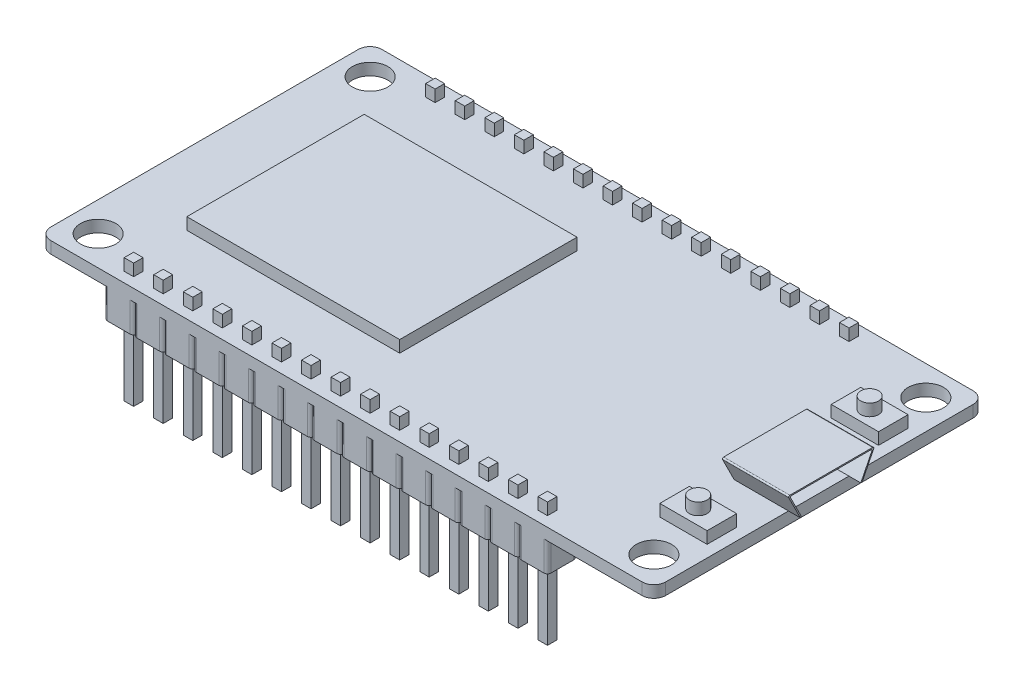
SolidWorks part; units mm, degrees
ref_plane "前视基准面" through (0, 0, 0) normal (0, 0, 1) x (1, 0, 0)
ref_plane "上视基准面" through (0, 0, 0) normal (0, 1, 0) x (1, 0, 0)
ref_plane "右视基准面" through (0, 0, 0) normal (1, 0, 0) x (0, 0, -1)
other "Configuration Table"
sketch "草图1" plane through (0, 0, 0) normal (0, 1, 0) x (1, 0, 0)
  line L0 (0, 0) -> (-18936.8297, 0) construction
  line L1 (0, 0) -> (0, -18936.8297) construction
  line L2 (-26, -14) -> (-26, 14)
  line L3 (-26, 14) -> (26, 14)
  line L4 (26, 14) -> (26, -14)
  line L5 (-26, -14) -> (26, -14)
  circle A0 centre (-23.5, -11.5) radius 1.5
  circle A1 centre (23.5, -11.5) radius 1.5
  circle A2 centre (23.5, 11.5) radius 1.5
  circle A3 centre (-23.5, 11.5) radius 1.5
  point P10 (26, 0)
  point P11 (-26, 0)
  point P15 (-16.0179, -2.0506)
  dimension "D3" = 3
  dimension "D1" = 52
  dimension "D2" = 28
  dimension "D4" = 2.5
  dimension "D5" = 2.5
extrude "凸台-拉伸1" add sketch "草图1" along normal blind 1
fillet "圆角1" radius 1 4 edges at (-26, 0.5, -14) (26, 0.5, -14) (26, 0.5, 14) (-26, 0.5, 14)
sketch "草图2" plane through (0, 0, 0) normal (0, 1, 0) x (1, 0, 0)
  line L0 (0, 0) -> (-50000, 0) construction
  line L1 (0, 0) -> (0, -50000) construction
  line L2 (-20, 7.5) -> (-20, -7.5)
  line L3 (-20, -7.5) -> (-2, -7.5)
  line L4 (-2, -7.5) -> (-2, 7.5)
  line L5 (-2, 7.5) -> (-20, 7.5)
  line L6 (-26, 13) -> (-26, -13) construction
  dimension "D1" = 6
  dimension "D2" = 18
  dimension "D3" = 15
extrude "凸台-拉伸2" add sketch "草图2" along normal blind 2
ref_plane "基准面1" through (26, 0, 0) normal (1, 0, 0) x (0, 0, -1)
sketch "草图3" plane through (26, 0, 0) normal (1, 0, 0) x (0, 0, -1)
  line L0 (0, 0) -> (0, -50000) construction
  line L1 (0, 0) -> (-50000, 0) construction
  line L4 (-7.5, 1) -> (7.5, 1) construction
  line L5 (2.5, 1) -> (3.5, 3)
  line L6 (3.5, 3) -> (-3.5, 3)
  line L7 (-3.5, 3) -> (-2.5, 1)
  line L8 (-2.6118, 1) -> (-3.6618, 3.1)
  line L9 (-3.6618, 3.1) -> (3.6618, 3.1)
  line L10 (3.6618, 3.1) -> (2.6118, 1)
  line L11 (2.6118, 1) -> (2.5, 1)
  line L12 (-2.5, 1) -> (-2.6118, 1)
  dimension "D2" = 5
  dimension "D3" = 7
  dimension "D4" = 0.1
  dimension "D5" = 0.1
  dimension "D6" = 0.1
extrude "凸台-拉伸3" add sketch "草图3" along normal blind 1 and the other way blind 4.5
ref_plane "基准面2" through (21.5, 0, 0) normal (1, 0, 0) x (0, 0, -1)
sketch "草图4" plane through (21.5, 0, 0) normal (1, 0, 0) x (0, 0, -1)
  line L0 (-3.6618, 3.1) -> (-2.6118, 1)
  line L1 (-2.6118, 1) -> (2.6118, 1)
  line L2 (2.6118, 1) -> (3.6618, 3.1)
  line L3 (3.6618, 3.1) -> (-3.6618, 3.1)
extrude "凸台-拉伸4" add sketch "草图4" against normal blind 0.1
fillet "圆角2" radius 0.1 4 edges at (24.25, 3, -3.5) (24.2, 3.1, -3.6618) (24.25, 3, 3.5) (24.2, 3.1, 3.6618)
sketch "草图5" plane through (0, 0, 0) normal (0, 1, 0) x (1, 0, 0)
  line L0 (0, 0) -> (-50000, 0) construction
  line L1 (21, 8.5) -> (21, 6)
  line L2 (21, 6) -> (25, 6)
  line L3 (25, 6) -> (25, 8.5)
  line L4 (25, 8.5) -> (21, 8.5)
  line L5 (25, -6) -> (25, -8.5)
  line L6 (21, -6) -> (25, -6)
  line L7 (21, -8.5) -> (21, -6)
  line L8 (25, -8.5) -> (21, -8.5)
  line L10 (26, -13) -> (26, -2.6118) construction
  line L11 (-25, -14) -> (25, -14) construction
  dimension "D1" = 4
  dimension "D2" = 2.5
  dimension "D3" = 1
  dimension "D4" = 5.5
extrude "凸台-拉伸5" add sketch "草图5" along normal blind 2
sketch "草图6" plane through (0, 0, 0) normal (0, 1, 0) x (1, 0, 0)
  line L0 (0, 0) -> (-50000, 0) construction
  line L1 (23, 6) -> (23, -49994) construction
  line L2 (21, 6) -> (25, 6) construction
  line L3 (25, 7.25) -> (-49975, 7.25) construction
  line L4 (25, 6) -> (25, 8.5) construction
  circle A0 centre (23, 7.25) radius 0.75
  circle A1 centre (23, -7.25) radius 0.75
  point P7 (23, 6)
  point P12 (25, 7.25)
  dimension "D1" = 1.5
extrude "凸台-拉伸6" add sketch "草图6" along normal blind 3
sketch "草图7" plane through (0, 0, 0) normal (0, 1, 0) x (1, 0, 0)
  line L0 (0, 0) -> (-50000, 0) construction
  line L1 (-19.65, 13.15) -> (-19.65, 12.35)
  line L2 (-19.65, 12.35) -> (-18.85, 12.35)
  line L3 (-18.85, 12.35) -> (-18.85, 13.15)
  line L4 (-18.85, 13.15) -> (-19.65, 13.15)
  line L5 (25, 14) -> (-25, 14) construction
  line L6 (-20.5, 14) -> (-20.5, 11.5) construction
  line L7 (-20.5, 11.5) -> (-18, 11.5) construction
  line L8 (-18, 11.5) -> (-18, 14) construction
  line L9 (-18, 14) -> (-20.5, 14) construction
  line L10 (-26, 13) -> (-26, -13) construction
  line L11 (-18.85, -12.35) -> (-18.85, -13.15)
  line L12 (-18.85, -13.15) -> (-19.65, -13.15)
  line L13 (-19.65, -13.15) -> (-19.65, -12.35)
  line L14 (-19.65, -12.35) -> (-18.85, -12.35)
  line L15 (-17.15, 13.15) -> (-17.15, 12.35)
  line L16 (-16.35, 13.15) -> (-17.15, 13.15)
  line L17 (-16.35, 12.35) -> (-16.35, 13.15)
  line L18 (-17.15, 12.35) -> (-16.35, 12.35)
  line L19 (-17.15, -12.35) -> (-16.35, -12.35)
  line L20 (-17.15, -13.15) -> (-17.15, -12.35)
  line L21 (-16.35, -13.15) -> (-17.15, -13.15)
  line L22 (-16.35, -12.35) -> (-16.35, -13.15)
  line L23 (-14.65, 13.15) -> (-14.65, 12.35)
  line L24 (-13.85, 13.15) -> (-14.65, 13.15)
  line L25 (-13.85, 12.35) -> (-13.85, 13.15)
  line L26 (-14.65, 12.35) -> (-13.85, 12.35)
  line L27 (-14.65, -12.35) -> (-13.85, -12.35)
  line L28 (-14.65, -13.15) -> (-14.65, -12.35)
  line L29 (-13.85, -13.15) -> (-14.65, -13.15)
  line L30 (-13.85, -12.35) -> (-13.85, -13.15)
  line L31 (-12.15, 13.15) -> (-12.15, 12.35)
  line L32 (-11.35, 13.15) -> (-12.15, 13.15)
  line L33 (-11.35, 12.35) -> (-11.35, 13.15)
  line L34 (-12.15, 12.35) -> (-11.35, 12.35)
  line L35 (-12.15, -12.35) -> (-11.35, -12.35)
  line L36 (-12.15, -13.15) -> (-12.15, -12.35)
  line L37 (-11.35, -13.15) -> (-12.15, -13.15)
  line L38 (-11.35, -12.35) -> (-11.35, -13.15)
  line L39 (-9.65, 13.15) -> (-9.65, 12.35)
  line L40 (-8.85, 13.15) -> (-9.65, 13.15)
  line L41 (-8.85, 12.35) -> (-8.85, 13.15)
  line L42 (-9.65, 12.35) -> (-8.85, 12.35)
  line L43 (-9.65, -12.35) -> (-8.85, -12.35)
  line L44 (-9.65, -13.15) -> (-9.65, -12.35)
  line L45 (-8.85, -13.15) -> (-9.65, -13.15)
  line L46 (-8.85, -12.35) -> (-8.85, -13.15)
  line L47 (-7.15, 13.15) -> (-7.15, 12.35)
  line L48 (-6.35, 13.15) -> (-7.15, 13.15)
  line L49 (-6.35, 12.35) -> (-6.35, 13.15)
  line L50 (-7.15, 12.35) -> (-6.35, 12.35)
  line L51 (-7.15, -12.35) -> (-6.35, -12.35)
  line L52 (-7.15, -13.15) -> (-7.15, -12.35)
  line L53 (-6.35, -13.15) -> (-7.15, -13.15)
  line L54 (-6.35, -12.35) -> (-6.35, -13.15)
  line L55 (-4.65, 13.15) -> (-4.65, 12.35)
  line L56 (-3.85, 13.15) -> (-4.65, 13.15)
  line L57 (-3.85, 12.35) -> (-3.85, 13.15)
  line L58 (-4.65, 12.35) -> (-3.85, 12.35)
  line L59 (-4.65, -12.35) -> (-3.85, -12.35)
  line L60 (-4.65, -13.15) -> (-4.65, -12.35)
  line L61 (-3.85, -13.15) -> (-4.65, -13.15)
  line L62 (-3.85, -12.35) -> (-3.85, -13.15)
  line L63 (-2.15, 13.15) -> (-2.15, 12.35)
  line L64 (-1.35, 13.15) -> (-2.15, 13.15)
  line L65 (-1.35, 12.35) -> (-1.35, 13.15)
  line L66 (-2.15, 12.35) -> (-1.35, 12.35)
  line L67 (-2.15, -12.35) -> (-1.35, -12.35)
  line L68 (-2.15, -13.15) -> (-2.15, -12.35)
  line L69 (-1.35, -13.15) -> (-2.15, -13.15)
  line L70 (-1.35, -12.35) -> (-1.35, -13.15)
  line L71 (0.35, 13.15) -> (0.35, 12.35)
  line L72 (1.15, 13.15) -> (0.35, 13.15)
  line L73 (1.15, 12.35) -> (1.15, 13.15)
  line L74 (0.35, 12.35) -> (1.15, 12.35)
  line L75 (0.35, -12.35) -> (1.15, -12.35)
  line L76 (0.35, -13.15) -> (0.35, -12.35)
  line L77 (1.15, -13.15) -> (0.35, -13.15)
  line L78 (1.15, -12.35) -> (1.15, -13.15)
  line L79 (2.85, 13.15) -> (2.85, 12.35)
  line L80 (3.65, 13.15) -> (2.85, 13.15)
  line L81 (3.65, 12.35) -> (3.65, 13.15)
  line L82 (2.85, 12.35) -> (3.65, 12.35)
  line L83 (2.85, -12.35) -> (3.65, -12.35)
  line L84 (2.85, -13.15) -> (2.85, -12.35)
  line L85 (3.65, -13.15) -> (2.85, -13.15)
  line L86 (3.65, -12.35) -> (3.65, -13.15)
  line L87 (5.35, 13.15) -> (5.35, 12.35)
  line L88 (6.15, 13.15) -> (5.35, 13.15)
  line L89 (6.15, 12.35) -> (6.15, 13.15)
  line L90 (5.35, 12.35) -> (6.15, 12.35)
  line L91 (5.35, -12.35) -> (6.15, -12.35)
  line L92 (5.35, -13.15) -> (5.35, -12.35)
  line L93 (6.15, -13.15) -> (5.35, -13.15)
  line L94 (6.15, -12.35) -> (6.15, -13.15)
  line L95 (7.85, 13.15) -> (7.85, 12.35)
  line L96 (8.65, 13.15) -> (7.85, 13.15)
  line L97 (8.65, 12.35) -> (8.65, 13.15)
  line L98 (7.85, 12.35) -> (8.65, 12.35)
  line L99 (7.85, -12.35) -> (8.65, -12.35)
  line L100 (7.85, -13.15) -> (7.85, -12.35)
  line L101 (8.65, -13.15) -> (7.85, -13.15)
  line L102 (8.65, -12.35) -> (8.65, -13.15)
  line L103 (10.35, 13.15) -> (10.35, 12.35)
  line L104 (11.15, 13.15) -> (10.35, 13.15)
  line L105 (11.15, 12.35) -> (11.15, 13.15)
  line L106 (10.35, 12.35) -> (11.15, 12.35)
  line L107 (10.35, -12.35) -> (11.15, -12.35)
  line L108 (10.35, -13.15) -> (10.35, -12.35)
  line L109 (11.15, -13.15) -> (10.35, -13.15)
  line L110 (11.15, -12.35) -> (11.15, -13.15)
  line L111 (12.85, 13.15) -> (12.85, 12.35)
  line L112 (13.65, 13.15) -> (12.85, 13.15)
  line L113 (13.65, 12.35) -> (13.65, 13.15)
  line L114 (12.85, 12.35) -> (13.65, 12.35)
  line L115 (12.85, -12.35) -> (13.65, -12.35)
  line L116 (12.85, -13.15) -> (12.85, -12.35)
  line L117 (13.65, -13.15) -> (12.85, -13.15)
  line L118 (13.65, -12.35) -> (13.65, -13.15)
  line L119 (15.35, 13.15) -> (15.35, 12.35)
  line L120 (16.15, 13.15) -> (15.35, 13.15)
  line L121 (16.15, 12.35) -> (16.15, 13.15)
  line L122 (15.35, 12.35) -> (16.15, 12.35)
  line L123 (15.35, -12.35) -> (16.15, -12.35)
  line L124 (15.35, -13.15) -> (15.35, -12.35)
  line L125 (16.15, -13.15) -> (15.35, -13.15)
  line L126 (16.15, -12.35) -> (16.15, -13.15)
  point P20 (15.75, 0)
  point P30 (18.25, 0)
  point P39 (20.75, 0)
  point P48 (23.25, 0)
  point P57 (25.75, 0)
  point P66 (28.25, 0)
  point P75 (30.75, 0)
  point P84 (33.25, 0)
  point P93 (35.75, 0)
  point P102 (38.25, 0)
  point P111 (40.75, 0)
  point P120 (43.25, 0)
  point P129 (45.75, 0)
  point P138 (48.25, 0)
  point P147 (50.75, 0)
  dimension "D1" = 0.8
  dimension "D2" = 0.8
  dimension "D3" = 0.85
  dimension "D4" = 2.5
  dimension "D5" = 2.5
  dimension "D6" = 5.5
  dimension "D7" = 0.85
  dimension "D8" = 15
extrude "凸台-拉伸7" add sketch "草图7" against normal blind 8.5 and the other way blind 2
sketch "草图8" plane through (0, 0, 0) normal (0, 1, 0) x (1, 0, 0)
  line L0 (-20.5, 13.7) -> (-20.5, 11.8)
  line L1 (25, 14) -> (-25, 14) construction
  line L2 (-20.2, 11.5) -> (-18.3, 11.5)
  line L3 (-18, 11.8) -> (-18, 13.7)
  line L4 (-18.3, 14) -> (-20.2, 14)
  line L5 (-19.65, 13.15) -> (-19.65, 12.35) construction
  line L6 (0, 0) -> (50000, 0) construction
  line L7 (-20.2, -11.5) -> (-18.3, -11.5)
  line L8 (-20.5, -13.7) -> (-20.5, -11.8)
  line L9 (-18.3, -14) -> (-20.2, -14)
  line L10 (-18, -11.8) -> (-18, -13.7)
  line L11 (-15.8, 14) -> (-17.7, 14)
  line L12 (-18, 13.7) -> (-18, 11.8)
  line L13 (-17.7, 11.5) -> (-15.8, 11.5)
  line L14 (-15.5, 11.8) -> (-15.5, 13.7)
  line L15 (-17.7, -11.5) -> (-15.8, -11.5)
  line L16 (-15.5, -11.8) -> (-15.5, -13.7)
  line L17 (-15.8, -14) -> (-17.7, -14)
  line L18 (-18, -13.7) -> (-18, -11.8)
  line L19 (-13.3, 14) -> (-15.2, 14)
  line L20 (-15.5, 13.7) -> (-15.5, 11.8)
  line L21 (-15.2, 11.5) -> (-13.3, 11.5)
  line L22 (-13, 11.8) -> (-13, 13.7)
  line L23 (-15.2, -11.5) -> (-13.3, -11.5)
  line L24 (-13, -11.8) -> (-13, -13.7)
  line L25 (-13.3, -14) -> (-15.2, -14)
  line L26 (-15.5, -13.7) -> (-15.5, -11.8)
  line L27 (-10.8, 14) -> (-12.7, 14)
  line L28 (-13, 13.7) -> (-13, 11.8)
  line L29 (-12.7, 11.5) -> (-10.8, 11.5)
  line L30 (-10.5, 11.8) -> (-10.5, 13.7)
  line L31 (-12.7, -11.5) -> (-10.8, -11.5)
  line L32 (-10.5, -11.8) -> (-10.5, -13.7)
  line L33 (-10.8, -14) -> (-12.7, -14)
  line L34 (-13, -13.7) -> (-13, -11.8)
  line L35 (-8.3, 14) -> (-10.2, 14)
  line L36 (-10.5, 13.7) -> (-10.5, 11.8)
  line L37 (-10.2, 11.5) -> (-8.3, 11.5)
  line L38 (-8, 11.8) -> (-8, 13.7)
  line L39 (-10.2, -11.5) -> (-8.3, -11.5)
  line L40 (-8, -11.8) -> (-8, -13.7)
  line L41 (-8.3, -14) -> (-10.2, -14)
  line L42 (-10.5, -13.7) -> (-10.5, -11.8)
  line L43 (-5.8, 14) -> (-7.7, 14)
  line L44 (-8, 13.7) -> (-8, 11.8)
  line L45 (-7.7, 11.5) -> (-5.8, 11.5)
  line L46 (-5.5, 11.8) -> (-5.5, 13.7)
  line L47 (-7.7, -11.5) -> (-5.8, -11.5)
  line L48 (-5.5, -11.8) -> (-5.5, -13.7)
  line L49 (-5.8, -14) -> (-7.7, -14)
  line L50 (-8, -13.7) -> (-8, -11.8)
  line L51 (-3.3, 14) -> (-5.2, 14)
  line L52 (-5.5, 13.7) -> (-5.5, 11.8)
  line L53 (-5.2, 11.5) -> (-3.3, 11.5)
  line L54 (-3, 11.8) -> (-3, 13.7)
  line L55 (-5.2, -11.5) -> (-3.3, -11.5)
  line L56 (-3, -11.8) -> (-3, -13.7)
  line L57 (-3.3, -14) -> (-5.2, -14)
  line L58 (-5.5, -13.7) -> (-5.5, -11.8)
  line L59 (-0.8, 14) -> (-2.7, 14)
  line L60 (-3, 13.7) -> (-3, 11.8)
  line L61 (-2.7, 11.5) -> (-0.8, 11.5)
  line L62 (-0.5, 11.8) -> (-0.5, 13.7)
  line L63 (-2.7, -11.5) -> (-0.8, -11.5)
  line L64 (-0.5, -11.8) -> (-0.5, -13.7)
  line L65 (-0.8, -14) -> (-2.7, -14)
  line L66 (-3, -13.7) -> (-3, -11.8)
  line L67 (1.7, 14) -> (-0.2, 14)
  line L68 (-0.5, 13.7) -> (-0.5, 11.8)
  line L69 (-0.2, 11.5) -> (1.7, 11.5)
  line L70 (2, 11.8) -> (2, 13.7)
  line L71 (-0.2, -11.5) -> (1.7, -11.5)
  line L72 (2, -11.8) -> (2, -13.7)
  line L73 (1.7, -14) -> (-0.2, -14)
  line L74 (-0.5, -13.7) -> (-0.5, -11.8)
  line L75 (4.2, 14) -> (2.3, 14)
  line L76 (2, 13.7) -> (2, 11.8)
  line L77 (2.3, 11.5) -> (4.2, 11.5)
  line L78 (4.5, 11.8) -> (4.5, 13.7)
  line L79 (2.3, -11.5) -> (4.2, -11.5)
  line L80 (4.5, -11.8) -> (4.5, -13.7)
  line L81 (4.2, -14) -> (2.3, -14)
  line L82 (2, -13.7) -> (2, -11.8)
  line L83 (6.7, 14) -> (4.8, 14)
  line L84 (4.5, 13.7) -> (4.5, 11.8)
  line L85 (4.8, 11.5) -> (6.7, 11.5)
  line L86 (7, 11.8) -> (7, 13.7)
  line L87 (4.8, -11.5) -> (6.7, -11.5)
  line L88 (7, -11.8) -> (7, -13.7)
  line L89 (6.7, -14) -> (4.8, -14)
  line L90 (4.5, -13.7) -> (4.5, -11.8)
  line L91 (9.2, 14) -> (7.3, 14)
  line L92 (7, 13.7) -> (7, 11.8)
  line L93 (7.3, 11.5) -> (9.2, 11.5)
  line L94 (9.5, 11.8) -> (9.5, 13.7)
  line L95 (7.3, -11.5) -> (9.2, -11.5)
  line L96 (9.5, -11.8) -> (9.5, -13.7)
  line L97 (9.2, -14) -> (7.3, -14)
  line L98 (7, -13.7) -> (7, -11.8)
  line L99 (11.7, 14) -> (9.8, 14)
  line L100 (9.5, 13.7) -> (9.5, 11.8)
  line L101 (9.8, 11.5) -> (11.7, 11.5)
  line L102 (12, 11.8) -> (12, 13.7)
  line L103 (9.8, -11.5) -> (11.7, -11.5)
  line L104 (12, -11.8) -> (12, -13.7)
  line L105 (11.7, -14) -> (9.8, -14)
  line L106 (9.5, -13.7) -> (9.5, -11.8)
  line L107 (14.2, 14) -> (12.3, 14)
  line L108 (12, 13.7) -> (12, 11.8)
  line L109 (12.3, 11.5) -> (14.2, 11.5)
  line L110 (14.5, 11.8) -> (14.5, 13.7)
  line L111 (12.3, -11.5) -> (14.2, -11.5)
  line L112 (14.5, -11.8) -> (14.5, -13.7)
  line L113 (14.2, -14) -> (12.3, -14)
  line L114 (12, -13.7) -> (12, -11.8)
  line L115 (16.7, 14) -> (14.8, 14)
  line L116 (14.5, 13.7) -> (14.5, 11.8)
  line L117 (14.8, 11.5) -> (16.7, 11.5)
  line L118 (17, 11.8) -> (17, 13.7)
  line L119 (14.8, -11.5) -> (16.7, -11.5)
  line L120 (17, -11.8) -> (17, -13.7)
  line L121 (16.7, -14) -> (14.8, -14)
  line L122 (14.5, -13.7) -> (14.5, -11.8)
  arc A0 (-20.5, 11.8) -> (-20.2, 11.5) centre (-20.2, 11.8) ccw
  arc A1 (-18.3, 11.5) -> (-18, 11.8) centre (-18.3, 11.8) ccw
  arc A2 (-18, 13.7) -> (-18.3, 14) centre (-18.3, 13.7) ccw
  arc A3 (-20.5, 13.7) -> (-20.2, 14) centre (-20.2, 13.7) cw
  arc A4 (-18.3, -11.5) -> (-18, -11.8) centre (-18.3, -11.8) cw
  arc A5 (-18.3, -14) -> (-18, -13.7) centre (-18.3, -13.7) ccw
  arc A6 (-20.5, -13.7) -> (-20.2, -14) centre (-20.2, -13.7) ccw
  arc A7 (-20.2, -11.5) -> (-20.5, -11.8) centre (-20.2, -11.8) ccw
  arc A8 (-18, 13.7) -> (-17.7, 14) centre (-17.7, 13.7) cw
  arc A9 (-15.5, 13.7) -> (-15.8, 14) centre (-15.8, 13.7) ccw
  arc A10 (-18, 11.8) -> (-17.7, 11.5) centre (-17.7, 11.8) ccw
  arc A11 (-15.8, 11.5) -> (-15.5, 11.8) centre (-15.8, 11.8) ccw
  arc A12 (-17.7, -11.5) -> (-18, -11.8) centre (-17.7, -11.8) ccw
  arc A13 (-15.8, -11.5) -> (-15.5, -11.8) centre (-15.8, -11.8) cw
  arc A14 (-15.8, -14) -> (-15.5, -13.7) centre (-15.8, -13.7) ccw
  arc A15 (-18, -13.7) -> (-17.7, -14) centre (-17.7, -13.7) ccw
  arc A16 (-15.5, 13.7) -> (-15.2, 14) centre (-15.2, 13.7) cw
  arc A17 (-13, 13.7) -> (-13.3, 14) centre (-13.3, 13.7) ccw
  arc A18 (-15.5, 11.8) -> (-15.2, 11.5) centre (-15.2, 11.8) ccw
  arc A19 (-13.3, 11.5) -> (-13, 11.8) centre (-13.3, 11.8) ccw
  arc A20 (-15.2, -11.5) -> (-15.5, -11.8) centre (-15.2, -11.8) ccw
  arc A21 (-13.3, -11.5) -> (-13, -11.8) centre (-13.3, -11.8) cw
  arc A22 (-13.3, -14) -> (-13, -13.7) centre (-13.3, -13.7) ccw
  arc A23 (-15.5, -13.7) -> (-15.2, -14) centre (-15.2, -13.7) ccw
  arc A24 (-13, 13.7) -> (-12.7, 14) centre (-12.7, 13.7) cw
  arc A25 (-10.5, 13.7) -> (-10.8, 14) centre (-10.8, 13.7) ccw
  arc A26 (-13, 11.8) -> (-12.7, 11.5) centre (-12.7, 11.8) ccw
  arc A27 (-10.8, 11.5) -> (-10.5, 11.8) centre (-10.8, 11.8) ccw
  arc A28 (-12.7, -11.5) -> (-13, -11.8) centre (-12.7, -11.8) ccw
  arc A29 (-10.8, -11.5) -> (-10.5, -11.8) centre (-10.8, -11.8) cw
  arc A30 (-10.8, -14) -> (-10.5, -13.7) centre (-10.8, -13.7) ccw
  arc A31 (-13, -13.7) -> (-12.7, -14) centre (-12.7, -13.7) ccw
  arc A32 (-10.5, 13.7) -> (-10.2, 14) centre (-10.2, 13.7) cw
  arc A33 (-8, 13.7) -> (-8.3, 14) centre (-8.3, 13.7) ccw
  arc A34 (-10.5, 11.8) -> (-10.2, 11.5) centre (-10.2, 11.8) ccw
  arc A35 (-8.3, 11.5) -> (-8, 11.8) centre (-8.3, 11.8) ccw
  arc A36 (-10.2, -11.5) -> (-10.5, -11.8) centre (-10.2, -11.8) ccw
  arc A37 (-8.3, -11.5) -> (-8, -11.8) centre (-8.3, -11.8) cw
  arc A38 (-8.3, -14) -> (-8, -13.7) centre (-8.3, -13.7) ccw
  arc A39 (-10.5, -13.7) -> (-10.2, -14) centre (-10.2, -13.7) ccw
  arc A40 (-8, 13.7) -> (-7.7, 14) centre (-7.7, 13.7) cw
  arc A41 (-5.5, 13.7) -> (-5.8, 14) centre (-5.8, 13.7) ccw
  arc A42 (-8, 11.8) -> (-7.7, 11.5) centre (-7.7, 11.8) ccw
  arc A43 (-5.8, 11.5) -> (-5.5, 11.8) centre (-5.8, 11.8) ccw
  arc A44 (-7.7, -11.5) -> (-8, -11.8) centre (-7.7, -11.8) ccw
  arc A45 (-5.8, -11.5) -> (-5.5, -11.8) centre (-5.8, -11.8) cw
  arc A46 (-5.8, -14) -> (-5.5, -13.7) centre (-5.8, -13.7) ccw
  arc A47 (-8, -13.7) -> (-7.7, -14) centre (-7.7, -13.7) ccw
  arc A48 (-5.5, 13.7) -> (-5.2, 14) centre (-5.2, 13.7) cw
  arc A49 (-3, 13.7) -> (-3.3, 14) centre (-3.3, 13.7) ccw
  arc A50 (-5.5, 11.8) -> (-5.2, 11.5) centre (-5.2, 11.8) ccw
  arc A51 (-3.3, 11.5) -> (-3, 11.8) centre (-3.3, 11.8) ccw
  arc A52 (-5.2, -11.5) -> (-5.5, -11.8) centre (-5.2, -11.8) ccw
  arc A53 (-3.3, -11.5) -> (-3, -11.8) centre (-3.3, -11.8) cw
  arc A54 (-3.3, -14) -> (-3, -13.7) centre (-3.3, -13.7) ccw
  arc A55 (-5.5, -13.7) -> (-5.2, -14) centre (-5.2, -13.7) ccw
  arc A56 (-3, 13.7) -> (-2.7, 14) centre (-2.7, 13.7) cw
  arc A57 (-0.5, 13.7) -> (-0.8, 14) centre (-0.8, 13.7) ccw
  arc A58 (-3, 11.8) -> (-2.7, 11.5) centre (-2.7, 11.8) ccw
  arc A59 (-0.8, 11.5) -> (-0.5, 11.8) centre (-0.8, 11.8) ccw
  arc A60 (-2.7, -11.5) -> (-3, -11.8) centre (-2.7, -11.8) ccw
  arc A61 (-0.8, -11.5) -> (-0.5, -11.8) centre (-0.8, -11.8) cw
  arc A62 (-0.8, -14) -> (-0.5, -13.7) centre (-0.8, -13.7) ccw
  arc A63 (-3, -13.7) -> (-2.7, -14) centre (-2.7, -13.7) ccw
  arc A64 (-0.5, 13.7) -> (-0.2, 14) centre (-0.2, 13.7) cw
  arc A65 (2, 13.7) -> (1.7, 14) centre (1.7, 13.7) ccw
  arc A66 (-0.5, 11.8) -> (-0.2, 11.5) centre (-0.2, 11.8) ccw
  arc A67 (1.7, 11.5) -> (2, 11.8) centre (1.7, 11.8) ccw
  arc A68 (-0.2, -11.5) -> (-0.5, -11.8) centre (-0.2, -11.8) ccw
  arc A69 (1.7, -11.5) -> (2, -11.8) centre (1.7, -11.8) cw
  arc A70 (1.7, -14) -> (2, -13.7) centre (1.7, -13.7) ccw
  arc A71 (-0.5, -13.7) -> (-0.2, -14) centre (-0.2, -13.7) ccw
  arc A72 (2, 13.7) -> (2.3, 14) centre (2.3, 13.7) cw
  arc A73 (4.5, 13.7) -> (4.2, 14) centre (4.2, 13.7) ccw
  arc A74 (2, 11.8) -> (2.3, 11.5) centre (2.3, 11.8) ccw
  arc A75 (4.2, 11.5) -> (4.5, 11.8) centre (4.2, 11.8) ccw
  arc A76 (2.3, -11.5) -> (2, -11.8) centre (2.3, -11.8) ccw
  arc A77 (4.2, -11.5) -> (4.5, -11.8) centre (4.2, -11.8) cw
  arc A78 (4.2, -14) -> (4.5, -13.7) centre (4.2, -13.7) ccw
  arc A79 (2, -13.7) -> (2.3, -14) centre (2.3, -13.7) ccw
  arc A80 (4.5, 13.7) -> (4.8, 14) centre (4.8, 13.7) cw
  arc A81 (7, 13.7) -> (6.7, 14) centre (6.7, 13.7) ccw
  arc A82 (4.5, 11.8) -> (4.8, 11.5) centre (4.8, 11.8) ccw
  arc A83 (6.7, 11.5) -> (7, 11.8) centre (6.7, 11.8) ccw
  arc A84 (4.8, -11.5) -> (4.5, -11.8) centre (4.8, -11.8) ccw
  arc A85 (6.7, -11.5) -> (7, -11.8) centre (6.7, -11.8) cw
  arc A86 (6.7, -14) -> (7, -13.7) centre (6.7, -13.7) ccw
  arc A87 (4.5, -13.7) -> (4.8, -14) centre (4.8, -13.7) ccw
  arc A88 (7, 13.7) -> (7.3, 14) centre (7.3, 13.7) cw
  arc A89 (9.5, 13.7) -> (9.2, 14) centre (9.2, 13.7) ccw
  arc A90 (7, 11.8) -> (7.3, 11.5) centre (7.3, 11.8) ccw
  arc A91 (9.2, 11.5) -> (9.5, 11.8) centre (9.2, 11.8) ccw
  arc A92 (7.3, -11.5) -> (7, -11.8) centre (7.3, -11.8) ccw
  arc A93 (9.2, -11.5) -> (9.5, -11.8) centre (9.2, -11.8) cw
  arc A94 (9.2, -14) -> (9.5, -13.7) centre (9.2, -13.7) ccw
  arc A95 (7, -13.7) -> (7.3, -14) centre (7.3, -13.7) ccw
  arc A96 (9.5, 13.7) -> (9.8, 14) centre (9.8, 13.7) cw
  arc A97 (12, 13.7) -> (11.7, 14) centre (11.7, 13.7) ccw
  arc A98 (9.5, 11.8) -> (9.8, 11.5) centre (9.8, 11.8) ccw
  arc A99 (11.7, 11.5) -> (12, 11.8) centre (11.7, 11.8) ccw
  arc A100 (9.8, -11.5) -> (9.5, -11.8) centre (9.8, -11.8) ccw
  arc A101 (11.7, -11.5) -> (12, -11.8) centre (11.7, -11.8) cw
  arc A102 (11.7, -14) -> (12, -13.7) centre (11.7, -13.7) ccw
  arc A103 (9.5, -13.7) -> (9.8, -14) centre (9.8, -13.7) ccw
  arc A104 (12, 13.7) -> (12.3, 14) centre (12.3, 13.7) cw
  arc A105 (14.5, 13.7) -> (14.2, 14) centre (14.2, 13.7) ccw
  arc A106 (12, 11.8) -> (12.3, 11.5) centre (12.3, 11.8) ccw
  arc A107 (14.2, 11.5) -> (14.5, 11.8) centre (14.2, 11.8) ccw
  arc A108 (12.3, -11.5) -> (12, -11.8) centre (12.3, -11.8) ccw
  arc A109 (14.2, -11.5) -> (14.5, -11.8) centre (14.2, -11.8) cw
  arc A110 (14.2, -14) -> (14.5, -13.7) centre (14.2, -13.7) ccw
  arc A111 (12, -13.7) -> (12.3, -14) centre (12.3, -13.7) ccw
  arc A112 (14.5, 13.7) -> (14.8, 14) centre (14.8, 13.7) cw
  arc A113 (17, 13.7) -> (16.7, 14) centre (16.7, 13.7) ccw
  arc A114 (14.5, 11.8) -> (14.8, 11.5) centre (14.8, 11.8) ccw
  arc A115 (16.7, 11.5) -> (17, 11.8) centre (16.7, 11.8) ccw
  arc A116 (14.8, -11.5) -> (14.5, -11.8) centre (14.8, -11.8) ccw
  arc A117 (16.7, -11.5) -> (17, -11.8) centre (16.7, -11.8) cw
  arc A118 (16.7, -14) -> (17, -13.7) centre (16.7, -13.7) ccw
  arc A119 (14.5, -13.7) -> (14.8, -14) centre (14.8, -13.7) ccw
  point P8 (-20.5, 12.75)
  point P18 (-20.5, 11.5)
  point P21 (-18, 11.5)
  point P24 (-18, 14)
  point P27 (-20.5, 14)
  point P30 (-18, -11.5)
  point P33 (-18, -14)
  point P36 (-20.5, -14)
  point P39 (-20.5, -11.5)
  point P40 (0, 0)
  point P41 (0, 0)
  point P378 (0, 0)
  point P379 (0, 0)
  point P380 (0, 0)
  dimension "D4" = 0.3
  dimension "D5" = 0.3
  dimension "D1" = 2.5
  dimension "D2" = 2.5
  dimension "D3" = 0.85
  dimension "D6" = 15
extrude "凸台-拉伸9" add sketch "草图8" against normal blind 2.5 contours L7 A7 L8 A6 L9 A5 L10 A4 | L10 A15 L17 A14 L16 A13 L15 A12 | L16 A23 L25 A22 L24 A21 L23 A20 | L24 A31 L33 A30 L32 A29 L31 A28 | L32 A39 L41 A38 L40 A37 L39 A36 | L40 A47 L49 A46 L48 A45 L47 A44 | L48 A55 L57 A54 L56 A53 L55 A52 | L56 A63 L65 A62 L64 A61 L63 A60 | L64 A71 L73 A70 L72 A69 L71 A68 | L72 A79 L81 A78 L80 A77 L79 A76 | L80 A87 L89 A86 L88 A85 L87 A84 | L104 A111 L113 A110 L112 A109 L111 A108 | L112 A119 L121 A118 L120 A117 L119 A116 | L117 A115 L118 A113 L115 A112 L110 A114 | L109 A107 L110 A105 L107 A104 L102 A106 | L101 A99 L102 A97 L99 A96 L94 A98 | L85 A83 L86 A81 L83 A80 L78 A82 | L77 A75 L78 A73 L75 A72 L70 A74 | L37 A35 L38 A33 L35 A32 L30 A34 | L21 A19 L22 A17 L19 A16 L14 A18 | L13 A11 L14 A9 L11 A8 L3 A10 | A3 L0 A0 L2 A1 L3 A2 L4 | L97 A95 L98 A92 L95 A93 L96 A94 | L61 A59 L62 A57 L59 A56 L60 A58 | L53 A51 L54 A49 L51 A48 L52 A50 | L45 A43 L46 A41 L43 A40 L44 A42
